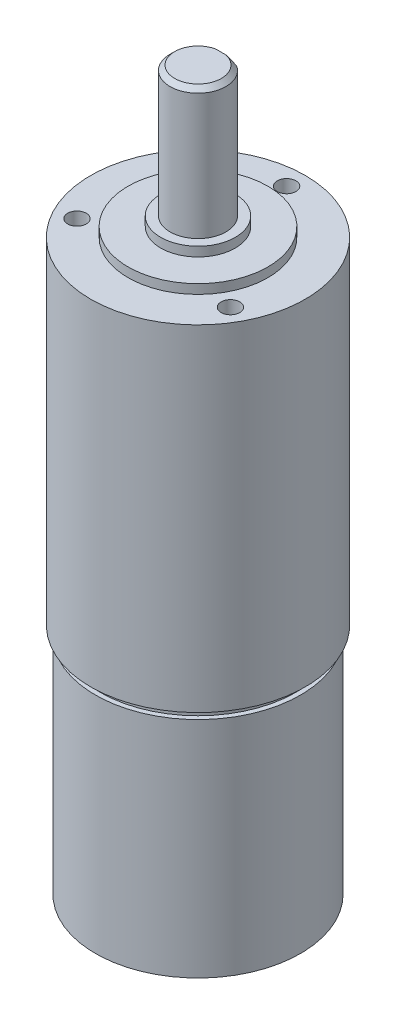
SolidWorks part; units mm, degrees
ref_plane "Plan de face" through (0, 0, 0) normal (0, 0, 1) x (1, 0, 0)
ref_plane "Plan de dessus" through (0, 0, 0) normal (0, 1, 0) x (1, 0, 0)
ref_plane "Plan de droite" through (0, 0, 0) normal (1, 0, 0) x (0, 0, -1)
sketch "Esquisse1" plane through (0, 0, 0) normal (0, 0, 1) x (1, 0, 0)
  line L0 (0, 0) -> (0, 79) construction
  line L1 (0, 0) -> (7.5, 0)
  line L2 (7.5, 0) -> (7.5, 2)
  line L3 (7.5, 2) -> (11, 2)
  line L4 (11, 2) -> (11, 26)
  line L5 (11, 26) -> (10.5, 26)
  line L6 (10.5, 26) -> (10.5, 27)
  line L7 (10.5, 27) -> (11.5, 27)
  line L8 (11.5, 27) -> (11.5, 63)
  line L9 (11.5, 63) -> (7.5, 63)
  line L10 (7.5, 63) -> (7.5, 64)
  line L11 (7.5, 64) -> (4, 64)
  line L12 (4, 64) -> (4, 65)
  line L13 (4, 65) -> (3, 65)
  line L14 (3, 65) -> (3, 79)
  line L15 (3, 79) -> (0, 79)
  line L16 (0, 0) -> (0, 79)
  dimension "D1" = 79
  dimension "D2" = 14
  dimension "D3" = 1
  dimension "D4" = 1
  dimension "D5" = 36
  dimension "D6" = 1
  dimension "D7" = 24
  dimension "D8" = 2
  dimension "D9" = 7.5
  dimension "D10" = 11
  dimension "D11" = 11.5
  dimension "D12" = 0.5
  dimension "D13" = 7.5
  dimension "D14" = 4
  dimension "D15" = 3
revolve "Révolution1" add sketch "Esquisse1" angle 360 about L0
sketch "Esquisse2" plane through (0, 79, 0) normal (0, 1, 0) x (1, 0, 0)
  line L0 (-1.75, 2.4367) -> (1.75, 2.4367)
  circle A0 centre (0, 0) radius 3 construction
  circle A1 centre (0, 0) radius 3 construction
  arc A2 (-1.75, 2.4367) -> (1.75, 2.4367) centre (0, 0) cw
  dimension "D1" = 3.5
extrude "Enlèv. mat.-Extru.2" cut sketch "Esquisse2" against normal blind 10
chamfer "Chanfrein1" distance 0.5 angle 45 1 edges at (0, 79, 3)
sketch "Esquisse3" plane through (0, 63, 0) normal (0, 1, 0) x (1, 0, 0)
  line L0 (0, 0) -> (0, 11.5) construction
  line L1 (0, 0) -> (8.2272, -4.75) construction
  line L2 (0, 0) -> (-8.2272, -4.75) construction
  circle A0 centre (0, 0) radius 11.5 construction
  circle A1 centre (0, 0) radius 9.5 construction
  circle A2 centre (0, 9.5) radius 1
  circle A3 centre (8.2272, -4.75) radius 1
  circle A4 centre (-8.2272, -4.75) radius 1
  dimension "D1" = 19
  dimension "D2" = 120
  dimension "D4" = 2
  dimension "D3" = 120
extrude "Enlèv. mat.-Extru.3" cut sketch "Esquisse3" against normal blind 4
